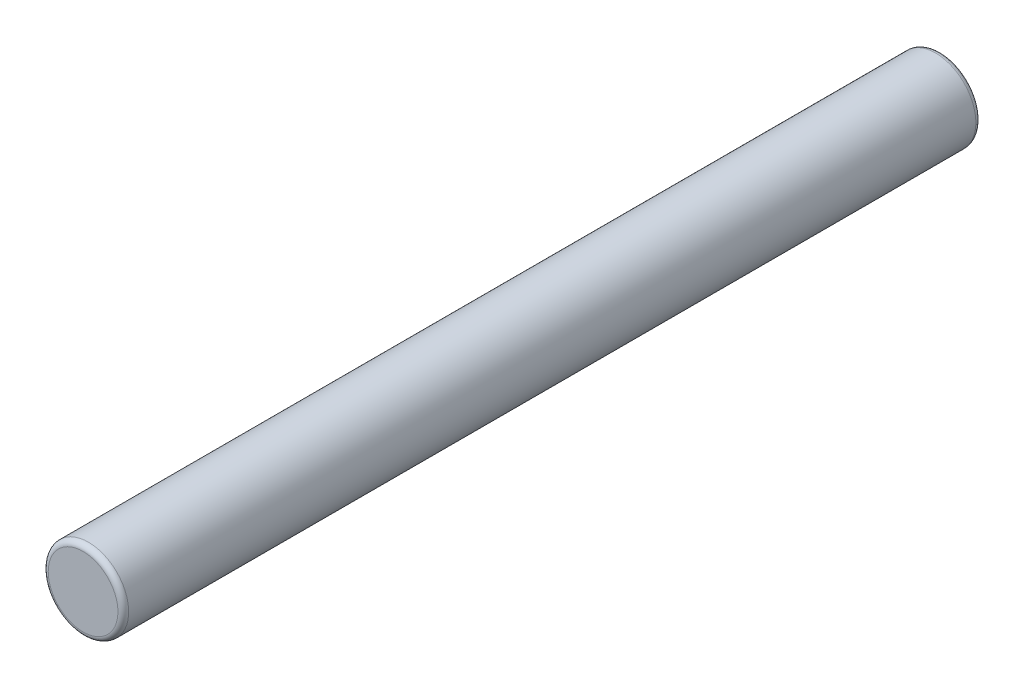
SolidWorks part; units mm, degrees
ref_plane "Front Plane" through (0, 0, 0) normal (0, 0, 1) x (1, 0, 0)
ref_plane "Top Plane" through (0, 0, 0) normal (0, 1, 0) x (1, 0, 0)
ref_plane "Right Plane" through (0, 0, 0) normal (1, 0, 0) x (0, 0, -1)
sketch "Sketch1" plane through (0, 0, 0) normal (0, 1, 0) x (1, 0, 0)
  line L0 (0, 0) -> (0, 16) construction
  line L1 (0, 0) -> (0, -16) construction
  line L2 (0, 16) -> (1.3, 16)
  line L3 (1.5, -15.8) -> (1.5, 15.8)
  line L4 (0, 16) -> (0, -16)
  line L5 (0, 0) -> (1.5, 0) construction
  line L6 (0, -16) -> (1.3, -16)
  arc A0 (1.5, 15.8) -> (1.3, 16) centre (1.3, 15.8) ccw
  arc A1 (1.5, -15.8) -> (1.3, -16) centre (1.3, -15.8) cw
  dimension "D3" = 0.2
  dimension "D1" = 3
  dimension "D2" = 32
revolve "Revolve1" add sketch "Sketch1" angle 360 about L4
